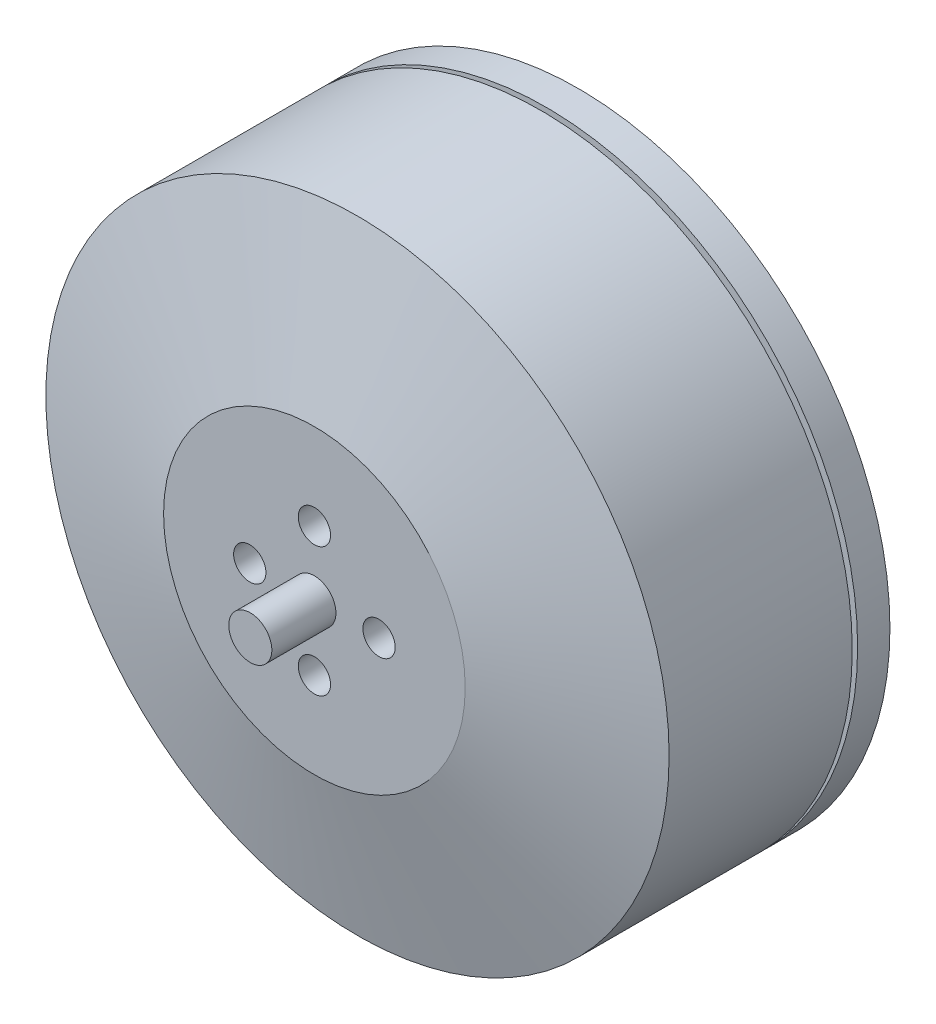
SolidWorks part; units mm, degrees
ref_plane "Front Plane" through (0, 0, 0) normal (0, 0, 1) x (1, 0, 0)
ref_plane "Top Plane" through (0, 0, 0) normal (0, 1, 0) x (1, 0, 0)
ref_plane "Right Plane" through (0, 0, 0) normal (1, 0, 0) x (0, 0, -1)
sketch "Sketch3" plane through (0, 0, 0) normal (1, 0, 0) x (0, 0, -1)
  line L0 (0, 83.7407) -> (0, -73.3704) construction
  line L1 (-29.5, 0) -> (-29.5, 14)
  line L2 (-29.5, 14) -> (-25.5, 28.93)
  line L3 (-25.5, 28.93) -> (-8.5, 28.93)
  line L4 (-8.5, 28.93) -> (-8.5, 26.93)
  line L5 (-8.5, 26.93) -> (-8, 26.93)
  line L6 (-8, 26.93) -> (-8, 28.93)
  line L7 (-8, 28.93) -> (-5, 28.93)
  line L8 (-5, 28.93) -> (0, 17.75)
  line L10 (-1.5, 0) -> (-29.5, 0)
  line L11 (-66.2834, 0) -> (25.0331, 0) construction
  line L12 (0, 17.75) -> (0, 9)
  line L13 (0, 9) -> (-1.5, 7.5)
  line L14 (-1.5, 7.5) -> (-1.5, 0)
  dimension "D1" = 28
  dimension "D2" = 57.86
  dimension "D3" = 4
  dimension "D4" = 5
  dimension "D5" = 3
  dimension "D6" = 0.5
  dimension "D7" = 35.5
  dimension "D8" = 2
  dimension "D9" = 1.5
  dimension "D10" = 15
  dimension "D11" = 18
  dimension "D12" = 29.5
revolve "Revolve1" add sketch "Sketch3" angle 360 about L11
sketch "Sketch4" plane through (0, 0, 29.5) normal (0, 0, 1) x (1, 0, 0)
  circle A0 centre (0, 0) radius 2
  dimension "D1" = 4
extrude "Boss-Extrude1" add sketch "Sketch4" along normal blind 5.95
sketch "Sketch5" plane through (0, 0, 29.5) normal (0, 0, 1) x (1, 0, 0)
  circle A0 centre (0, 0) radius 6
  circle A1 centre (0, 6) radius 1.5
  circle A2 centre (6, 0) radius 1.5
  circle A3 centre (0, -6) radius 1.5
  circle A4 centre (-6, 0) radius 1.5
  dimension "D1" = 12
  dimension "D2" = 3
extrude "Cut-Extrude1" cut sketch "Sketch5" against normal blind 5 contours A1 | A2 | A3 | A4
sketch "Sketch6" plane through (0, 0, 0) normal (0, 0, -1) x (-1, 0, 0)
  circle A0 centre (0, 0) radius 12.5
  circle A1 centre (0, 12.5) radius 1.5
  circle A2 centre (12.5, 0) radius 1.5
  circle A3 centre (0, -12.5) radius 1.5
  circle A4 centre (-12.5, 0) radius 1.5
  dimension "D1" = 25
  dimension "D2" = 3
extrude "Cut-Extrude2" cut sketch "Sketch6" against normal blind 5 contours A1 | A2 | A3 | A4
sketch "Sketch7" plane through (0, 0, 1.5) normal (0, 0, -1) x (-1, 0, 0)
  circle A0 centre (0, 0) radius 4.25
  dimension "D1" = 8.5
extrude "Boss-Extrude2" add sketch "Sketch7" along normal blind 4.3
sketch "Sketch8" plane through (0, 0, -2.8) normal (0, 0, -1) x (-1, 0, 0)
  circle A0 centre (0, 0) radius 2.8
  dimension "D1" = 5.6
extrude "Cut-Extrude3" cut sketch "Sketch8" against normal blind 0.1
sketch "Sketch9" plane through (0, 0, -2.7) normal (0, 0, -1) x (-1, 0, 0)
  line L1 (0, -1.1547) -> (1, -0.5774)
  line L2 (1, -0.5774) -> (1, 0.5774)
  line L3 (1, 0.5774) -> (0, 1.1547)
  line L4 (0, 1.1547) -> (-1, 0.5774)
  line L5 (-1, 0.5774) -> (-1, -0.5774)
  line L6 (-1, -0.5774) -> (0, -1.1547)
  circle A0 centre (0, 0) radius 1 construction
  dimension "D1" = 2
extrude "Cut-Extrude4" cut sketch "Sketch9" against normal blind 1.5
sketch "Sketch10" plane through (0, 0, 1.5) normal (0, 0, -1) x (-1, 0, 0)
  circle A0 centre (0, 0) radius 6.5
  circle A1 centre (0, 0) radius 5.5
  circle A2 centre (0, 0) radius 7.5 construction
  dimension "D1" = 1
  dimension "D2" = 1
extrude "Cut-Extrude5" cut sketch "Sketch10" against normal blind 0.1
